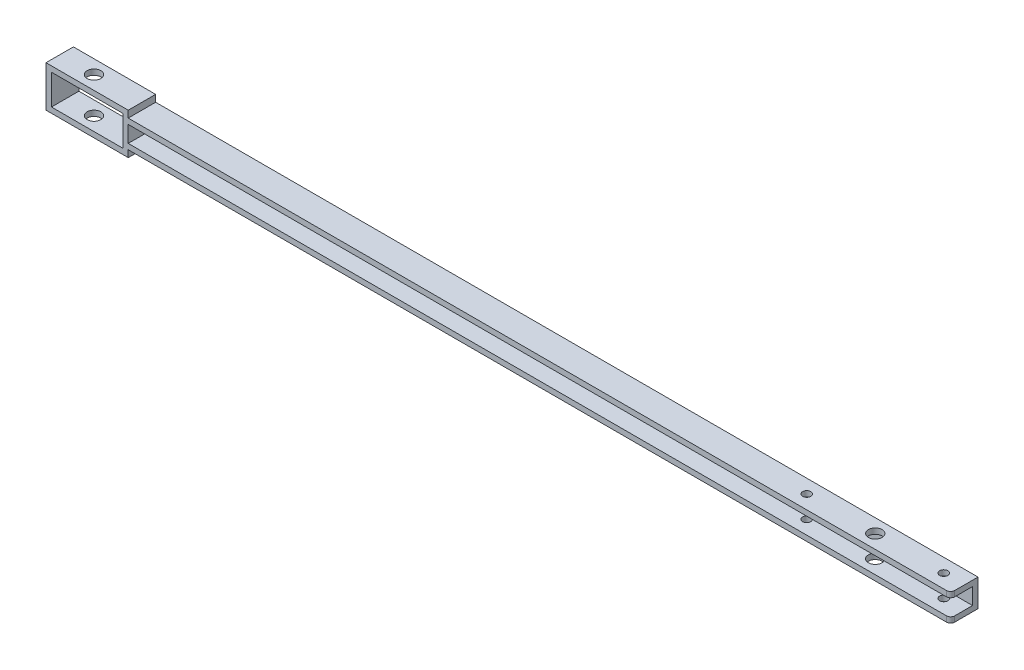
SolidWorks part; units mm, degrees
ref_plane "Front Plane" through (0, 0, 0) normal (0, 0, 1) x (1, 0, 0)
ref_plane "Top Plane" through (0, 0, 0) normal (0, 1, 0) x (1, 0, 0)
ref_plane "Right Plane" through (0, 0, 0) normal (1, 0, 0) x (0, 0, -1)
sketch "Sketch1" plane through (0, 0, 0) normal (0, 0, 1) x (1, 0, 0)
  line L1 (0, 0) -> (30, 0)
  line L2 (0, 0) -> (0, 15)
  line L3 (0, 15) -> (30, 15)
  line L4 (30, 0) -> (30, 15)
  line L5 (2, 13) -> (28, 13)
  line L6 (2, 13) -> (2, 2)
  line L7 (2, 2) -> (28, 2)
  line L8 (28, 13) -> (28, 2)
  dimension "D1" = 30
  dimension "D2" = 15
  dimension "D3" = 2
  dimension "D4" = 2
  dimension "D5" = 2
  dimension "D6" = 2
extrude "Boss-Extrude1" add sketch "Sketch1" along normal blind 10
sketch "Sketch3" plane through (0, 15, 0) normal (0, 1, 0) x (1, 0, 0)
  line L0 (0, -10) -> (30, -10)
  line L1 (30, -10) -> (0, -10) construction
  line L2 (30, 0) -> (0, 0) construction
  line L5 (30, -10) -> (30, 0) construction
  line L7 (15, -5) -> (30, -5) construction
  circle A0 centre (12.5, -5) radius 2.5
  dimension "D3" = 5
  dimension "D1" = 10
extrude "Cut-Extrude1" cut sketch "Sketch3" against normal blind 100 contours A0
sketch "Sketch5" plane through (0, 0, 0) normal (0, 0, -1) x (-1, 0, 0)
  line L2 (-30, 0) -> (-30, 15) construction
  line L5 (-30, 12.5) -> (-330, 12.5)
  line L6 (-30, 12.5) -> (-30, 2.5)
  line L7 (-30, 2.5) -> (-330, 2.5)
  line L8 (-330, 12.5) -> (-330, 2.5)
  dimension "D1" = 300
  dimension "D3" = 10
  dimension "D4" = 10
extrude "Boss-Extrude2" add sketch "Sketch5" against normal blind 10
sketch "Sketch6" plane through (330, 0, 0) normal (1, 0, 0) x (0, 0, -1)
  line L0 (-10, 12.5) -> (-10, 2.5) construction
  line L1 (-10, 10.5) -> (-2, 10.5)
  line L2 (-10, 10.5) -> (-10, 4.5)
  line L3 (-10, 4.5) -> (-2, 4.5)
  line L4 (-2, 10.5) -> (-2, 4.5)
  line L5 (0, 12.5) -> (0, 2.5) construction
  line L6 (-10, 12.5) -> (0, 12.5) construction
  line L7 (-10, 2.5) -> (0, 2.5) construction
  dimension "D1" = 2
  dimension "D2" = 2
  dimension "D3" = 2
extrude "Cut-Extrude2" cut sketch "Sketch6" against normal blind 300 contours L2 L1 L4 L3
sketch "Sketch7" plane through (0, 2.5, 0) normal (0, -1, 0) x (-1, 0, 0)
  circle A0 centre (-272.5, -5) radius 1.5
  circle A1 centre (-297.5, -5) radius 2.5
  circle A2 centre (-322.5, -5) radius 1.5
  dimension "D4" = 3
  dimension "D5" = 5
  dimension "D6" = 3
  dimension "D2" = 25
  dimension "D3" = 25
extrude "Cut-Extrude3" cut sketch "Sketch7" against normal blind 300
fillet "Fillet1" radius 1.5 2 edges at (330, 3.5, 10) (330, 11.5, 10)
sketch "Sketch8" plane through (0, 0, 2) normal (0, 0, 1) x (1, 0, 0)
  line L0 (30, 10.5) -> (330, 10.5) construction
  line L1 (41.5472, 10.5) -> (56.5472, 10.5)
  line L2 (41.5472, 10.5) -> (41.5472, 4.5)
  line L3 (41.5472, 4.5) -> (56.5472, 4.5)
  line L4 (56.5472, 10.5) -> (56.5472, 4.5)
  line L5 (30, 4.5) -> (330, 4.5) construction
  dimension "D1" = 15
extrude "Cut-Extrude4" cut sketch "Sketch8" against normal blind 0.5
sketch "Sketch11" plane through (0, 0, 2) normal (0, 0, 1) x (1, 0, 0)
  line L0 (270.4867, 6.1385) -> (269.1997, 18.1842)
  line L1 (30, 4.5) -> (328.5, 4.5) construction
  line L2 (262.4566, 4.5) -> (247.4566, 4.5)
  line L3 (262.4566, 4.5) -> (262.4566, 10.5)
  line L4 (262.4566, 10.5) -> (247.4566, 10.5)
  line L5 (247.4566, 4.5) -> (247.4566, 10.5)
  line L6 (56.5472, 10.5) -> (330, 10.5) construction
  line M4 (56.5472, 4.5) -> (330, 4.5)
  line M6 (330, 10.5) -> (56.5472, 10.5)
  dimension "D1" = 15
extrude "Cut-Extrude8" cut sketch "Sketch11" against normal blind 1 contours L5 L3 M4 M6
sketch "Sketch9" plane through (0, 0, 2) normal (0, 0, 1) x (1, 0, 0)
  line L0 (56.5472, 4.5) -> (247.4566, 4.5) construction
  line L1 (315.7744, 4.5) -> (300.7744, 4.5)
  line L2 (315.7744, 4.5) -> (315.7744, 10.5)
  line L3 (315.7744, 10.5) -> (300.7744, 10.5)
  line L4 (300.7744, 4.5) -> (300.7744, 10.5)
  line L5 (56.5472, 10.5) -> (247.4566, 10.5) construction
  dimension "D1" = 15
extrude "Cut-Extrude5" cut sketch "Sketch9" against normal blind 0.5
